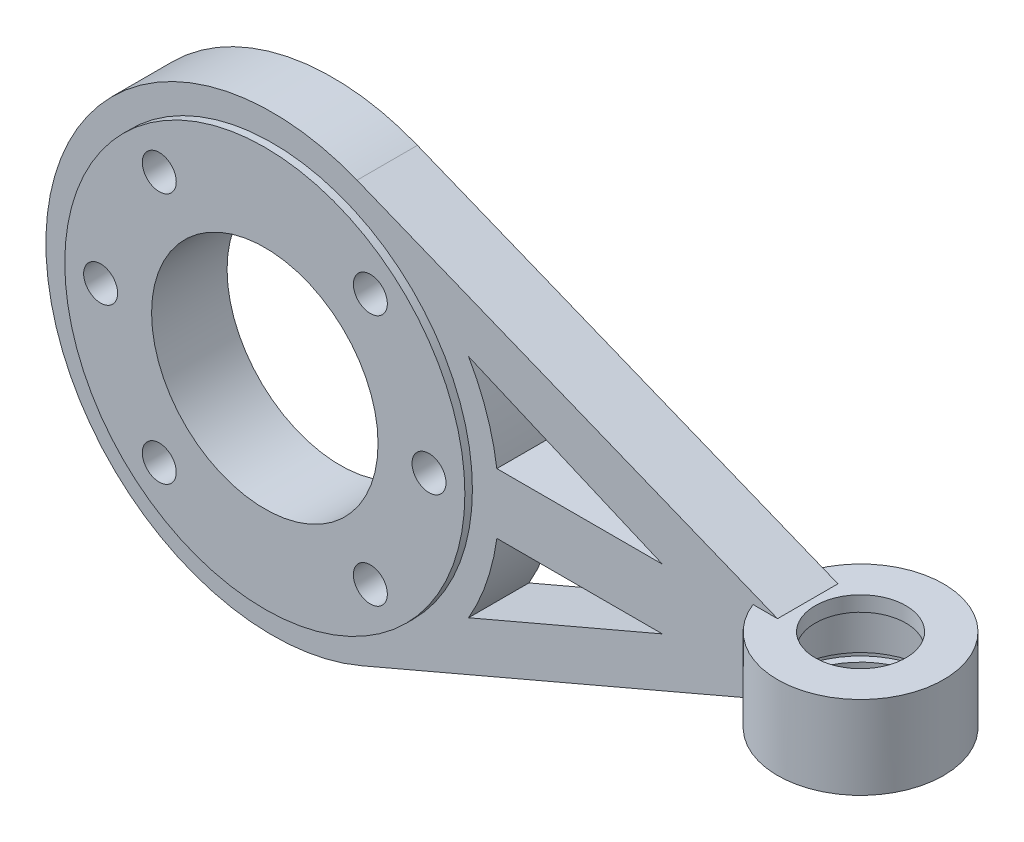
SolidWorks part; units mm, degrees
ref_plane "前视基准面" through (0, 0, 0) normal (0, 0, 1) x (1, 0, 0)
ref_plane "上视基准面" through (0, 0, 0) normal (0, 1, 0) x (1, 0, 0)
ref_plane "右视基准面" through (0, 0, 0) normal (1, 0, 0) x (0, 0, -1)
other "Configuration Table"
sketch "草图1" plane through (0, 0, 0) normal (0, 0, 1) x (1, 0, 0)
  circle A0 centre (0, 0) radius 30
  dimension "D1" = 60
extrude "凸台-拉伸1" add sketch "草图1" along normal blind 3
sketch "草图2" plane through (0, 0, 3) normal (0, 0, 1) x (1, 0, 0)
  line L0 (0, 0) -> (150.9371, 0) construction
  line L1 (73.9156, 22.7173) -> (73.9156, -21.6499) construction
  line L3 (62.9156, 5.375) -> (73.9156, 5.375)
  line L4 (62.9156, 5.375) -> (62.9156, -5.625)
  line L8 (62.9156, -5.625) -> (73.9156, -5.625)
  line L9 (73.9156, 5.375) -> (73.9156, -5.625)
  dimension "D2" = 11
  dimension "D1" = 73.9156
  dimension "D3" = 5.375
  dimension "D4" = 11
revolve "旋转1" add sketch "草图2" angle 360 about L1
sketch "草图3" plane through (0, 0, 3) normal (0, 0, 1) x (1, 0, 0)
  line L0 (11.2147, 27.825) -> (66.9156, 5.375)
  line L1 (11.801, -27.5814) -> (66.9156, -4)
  line L2 (73.9156, -5.625) -> (73.9156, 5.375) construction
  line L4 (66.9156, 5.375) -> (66.9156, -4)
  circle A1 centre (0, 0) radius 30
  arc A2 (11.2147, 27.825) -> (11.801, -27.5814) centre (0, 0) ccw
  dimension "D2" = 7
  dimension "D3" = 5.375
  dimension "D4" = 4
  dimension "D1" = 0
extrude "凸台-拉伸2" add sketch "草图3" along normal mid plane 8
sketch "草图4" plane through (0, -5.625, 0) normal (0, -1, 0) x (1, 0, 0)
  circle A0 centre (73.9156, 3) radius 6
  dimension "D1" = 12
extrude "切除-拉伸1" cut sketch "草图4" against normal blind 25
sketch "草图5" plane through (0, -5.625, 0) normal (0, -1, 0) x (1, 0, 0)
  circle A0 centre (73.9156, 3) radius 9
  dimension "D1" = 18
extrude "切除-拉伸2" cut sketch "草图5" against normal offset from surface (9 mm away) 2 up to face at (67.9156, 5.375, 3)
sketch "草图6" plane through (0, 3.375, 0) normal (0, -1, 0) x (1, 0, 0)
  circle A0 centre (73.9156, 3) radius 10
  circle A1 centre (73.9156, 3) radius 9 construction
  circle A2 centre (73.9156, 3) radius 9 construction
  circle A3 centre (73.9156, 3) radius 9
  circle M1 centre (73.9156, 3) radius 9
  dimension "D1" = 1
extrude "切除-拉伸3" cut sketch "草图6" along normal blind 1.1 from offset 6.75 contours A0 M1 | A3
ref_plane "基准面1" through (0, 0, 3) normal (0, 0, -1) x (-1, 0, 0)
sketch "草图8" plane through (0, 0, 3) normal (0, 0, -1) x (-1, 0, 0)
  circle A0 centre (0, 0) radius 26.5
  dimension "D1" = 53
extrude "凸台-拉伸3" add sketch "草图8" along normal mid plane 10
sketch "草图7" plane through (0, 0, 7) normal (0, 0, 1) x (1, 0, 0)
  line L0 (25.9897, -14.9845) -> (51.6627, -4)
  line L1 (0, 0) -> (55.8434, 0) construction
  line L2 (11.801, -27.5814) -> (63.6687, -5.3892) construction
  line L4 (29.7321, -4) -> (51.6627, -4)
  line L5 (29.7321, 4) -> (51.6627, 4)
  line L6 (25.9897, 14.9845) -> (51.6627, 4)
  circle A0 centre (0, 0) radius 15
  arc A1 (25.9897, -14.9845) -> (29.7321, -4) centre (0, 0) ccw
  arc A2 (25.9897, 14.9845) -> (29.7321, 4) centre (0, 0) cw
  dimension "D1" = 30
  dimension "D3" = 30
  dimension "D2" = 6
  dimension "D4" = 4
extrude "切除-拉伸4" cut sketch "草图7" against normal through all both and the other way through all
fillet "圆角1" [suppressed] radius 2
sketch "草图10" plane through (0, 0, 8) normal (0, 0, 1) x (1, 0, 0)
  line L0 (-42.7659, 0) -> (30.817, 0) construction
  line L1 (0, 0) -> (27.9613, -33.3229) construction
  line L2 (0, 31.5638) -> (0, -40.9894) construction
  circle A0 centre (21.75, 0) radius 2.25
  circle A1 centre (13.9806, -16.6615) radius 2.25
  circle A2 centre (-21.75, 0) radius 2.25
  circle A3 centre (-13.9806, -16.6615) radius 2.25
  circle A4 centre (13.9806, 16.6615) radius 2.25
  circle A5 centre (-13.9806, 16.6615) radius 2.25
  dimension "D2" = 4.5
  dimension "D3" = 4.5
  dimension "D1" = 50
  dimension "D4" = 21.75
  dimension "D5" = 21.75
extrude "切除-拉伸5" cut sketch "草图10" against normal blind 17
